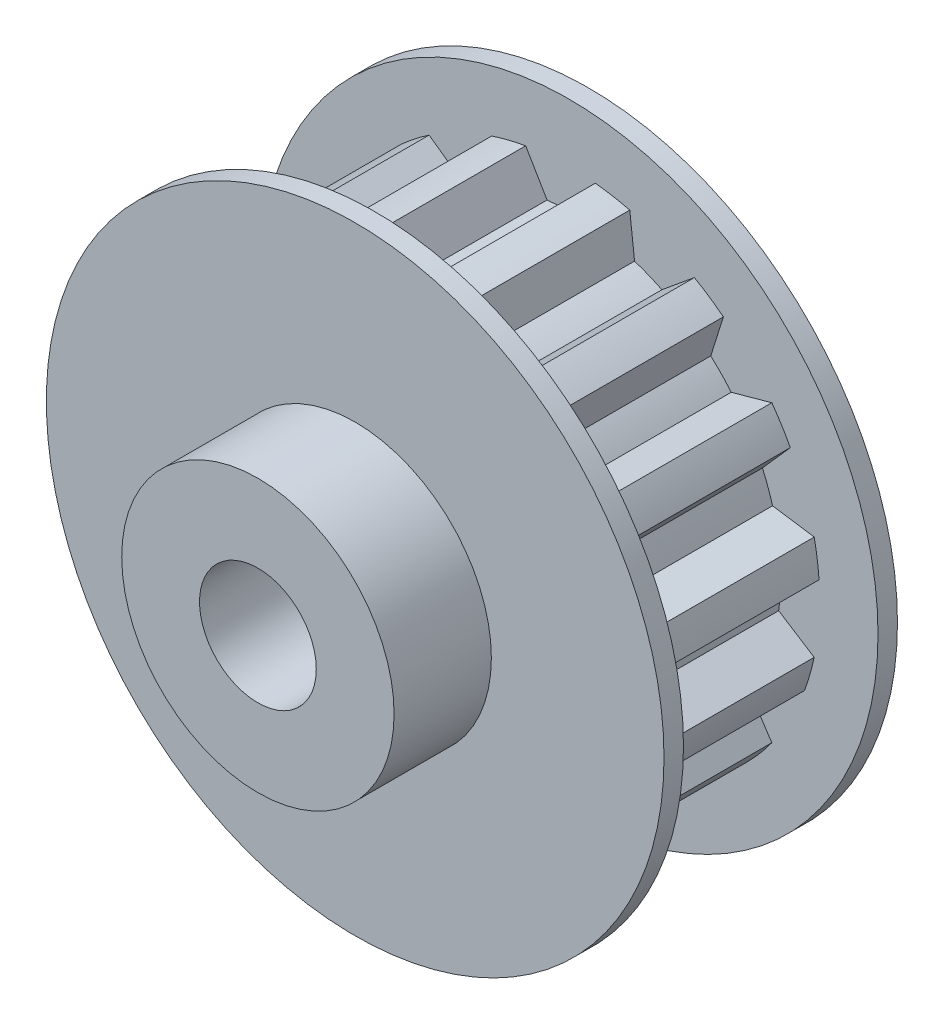
SolidWorks part; units mm, degrees
ref_plane "Front Plane" through (0, 0, 0) normal (0, 0, 1) x (1, 0, 0)
ref_plane "Top Plane" through (0, 0, 0) normal (0, 1, 0) x (1, 0, 0)
ref_plane "Right Plane" through (0, 0, 0) normal (1, 0, 0) x (0, 0, -1)
sketch "Sketch1" plane through (0, 0, 0) normal (0, 0, 1) x (1, 0, 0)
  circle A0 centre (0, 0) radius 15.875
  dimension "D1" = 31.75
extrude "Boss-Extrude1" add sketch "Sketch1" along normal blind 1
sketch "Sketch2" plane through (0, 0, 1) normal (0, 0, 1) x (1, 0, 0)
  line L0 (9.9348, -4.4233) -> (12.0985, -4.4035)
  line L1 (12.5937, -2.6769) -> (10.7692, -1.5135)
  line L2 (7.2768, -8.0817) -> (9.2615, -8.9437)
  line L3 (10.4161, -7.5677) -> (9.2225, -5.7629)
  line L4 (3.3606, -10.3427) -> (4.8231, -11.9375)
  line L5 (6.4375, -11.1501) -> (6.0812, -9.0158)
  line L6 (-1.1367, -10.8154) -> (-0.4493, -12.8672)
  line L7 (10.875, 0) -> (12.8436, 0.8981)
  line L8 (12.5937, 2.6769) -> (10.4537, 2.9976)
  line L9 (1.3458, -12.8045) -> (1.8884, -10.7098)
  line L10 (-5.4375, -9.418) -> (-5.644, -11.572)
  line L11 (-3.9786, -12.2449) -> (-2.6309, -10.552)
  line L12 (-8.7981, -6.3922) -> (-9.8628, -8.2759)
  line L13 (-8.6151, -9.568) -> (-6.6953, -8.5696)
  line L14 (-10.6374, -2.261) -> (-12.3762, -3.5488)
  line L15 (-11.7619, -5.2367) -> (-9.6021, -5.1055)
  line L16 (-10.6374, 2.261) -> (-12.7497, 1.7919)
  line L17 (-12.875, 0) -> (-10.8485, -0.7586)
  line L18 (-8.7981, 6.3922) -> (-10.9186, 6.8227)
  line L19 (-11.7619, 5.2367) -> (-10.2192, 3.7195)
  line L20 (-5.4375, 9.418) -> (-7.1996, 10.6739)
  line L21 (-8.6151, 9.568) -> (-7.8228, 7.5544)
  line L22 (-1.1367, 10.8154) -> (-2.2357, 12.6794)
  line L23 (-3.9786, 12.2449) -> (-4.0738, 10.0831)
  line L24 (3.3606, 10.3427) -> (3.1147, 12.4926)
  line L25 (1.3458, 12.8045) -> (0.3795, 10.8684)
  line L26 (7.2768, 8.0817) -> (7.9266, 10.1456)
  line L27 (6.4375, 11.1501) -> (4.7673, 9.7744)
  line L28 (9.9348, 4.4233) -> (11.368, 6.0444)
  line L29 (10.4161, 7.5677) -> (8.3307, 6.9903)
  arc A0 (12.8436, 0.8981) -> (12.5937, 2.6769) centre (0, 0) ccw
  arc A1 (12.0985, -4.4035) -> (12.5937, -2.6769) centre (0, 0) ccw
  circle A2 centre (0, 0) radius 15.875 construction
  arc A3 (10.4537, 2.9976) -> (9.9348, 4.4233) centre (0, 0) ccw
  arc A4 (10.7692, -1.5135) -> (10.875, 0) centre (0, 0) ccw
  arc A5 (9.2615, -8.9437) -> (10.4161, -7.5677) centre (0, 0) ccw
  arc A6 (9.2225, -5.7629) -> (9.9348, -4.4233) centre (0, 0) ccw
  arc A7 (4.8231, -11.9375) -> (6.4375, -11.1501) centre (0, 0) ccw
  arc A8 (6.0812, -9.0158) -> (7.2768, -8.0817) centre (0, 0) ccw
  arc A9 (-0.4493, -12.8672) -> (1.3458, -12.8045) centre (0, 0) ccw
  arc A10 (1.8884, -10.7098) -> (3.3606, -10.3427) centre (0, 0) ccw
  arc A11 (-5.644, -11.572) -> (-3.9786, -12.2449) centre (0, 0) ccw
  arc A12 (-2.6309, -10.552) -> (-1.1367, -10.8154) centre (0, 0) ccw
  arc A13 (-9.8628, -8.2759) -> (-8.6151, -9.568) centre (0, 0) ccw
  arc A14 (-6.6953, -8.5696) -> (-5.4375, -9.418) centre (0, 0) ccw
  arc A15 (-12.3762, -3.5488) -> (-11.7619, -5.2367) centre (0, 0) ccw
  arc A16 (-9.6021, -5.1055) -> (-8.7981, -6.3922) centre (0, 0) ccw
  arc A17 (-12.7497, 1.7919) -> (-12.875, 0) centre (0, 0) ccw
  arc A18 (-10.8485, -0.7586) -> (-10.6374, -2.261) centre (0, 0) ccw
  arc A19 (-10.9186, 6.8227) -> (-11.7619, 5.2367) centre (0, 0) ccw
  arc A20 (-10.2192, 3.7195) -> (-10.6374, 2.261) centre (0, 0) ccw
  arc A21 (-7.1996, 10.6739) -> (-8.6151, 9.568) centre (0, 0) ccw
  arc A22 (-7.8228, 7.5544) -> (-8.7981, 6.3922) centre (0, 0) ccw
  arc A23 (-2.2357, 12.6794) -> (-3.9786, 12.2449) centre (0, 0) ccw
  arc A24 (-4.0738, 10.0831) -> (-5.4375, 9.418) centre (0, 0) ccw
  arc A25 (3.1147, 12.4926) -> (1.3458, 12.8045) centre (0, 0) ccw
  arc A26 (0.3795, 10.8684) -> (-1.1367, 10.8154) centre (0, 0) ccw
  arc A27 (7.9266, 10.1456) -> (6.4375, 11.1501) centre (0, 0) ccw
  arc A28 (4.7673, 9.7744) -> (3.3606, 10.3427) centre (0, 0) ccw
  arc A29 (11.368, 6.0444) -> (10.4161, 7.5677) centre (0, 0) ccw
  arc A30 (8.3307, 6.9903) -> (7.2768, 8.0817) centre (0, 0) ccw
  dimension "D1" = 3
  dimension "D2" = 15
extrude "Boss-Extrude2" add sketch "Sketch2" along normal blind 10
sketch "Sketch3" plane through (0, 0, 11) normal (0, 0, 1) x (1, 0, 0)
  circle A0 centre (0, 0) radius 15.875
extrude "Boss-Extrude3" add sketch "Sketch3" along normal blind 1
sketch "Sketch4" plane through (0, 0, 12) normal (0, 0, 1) x (1, 0, 0)
  circle A0 centre (0, 0) radius 7
extrude "Boss-Extrude4" add sketch "Sketch4" along normal blind 5
sketch "Sketch5" plane through (0, 0, 17) normal (0, 0, 1) x (1, 0, 0)
  circle A0 centre (0, 0) radius 3
  dimension "D1" = 6
extrude "Cut-Extrude1" cut sketch "Sketch5" against normal up to next
